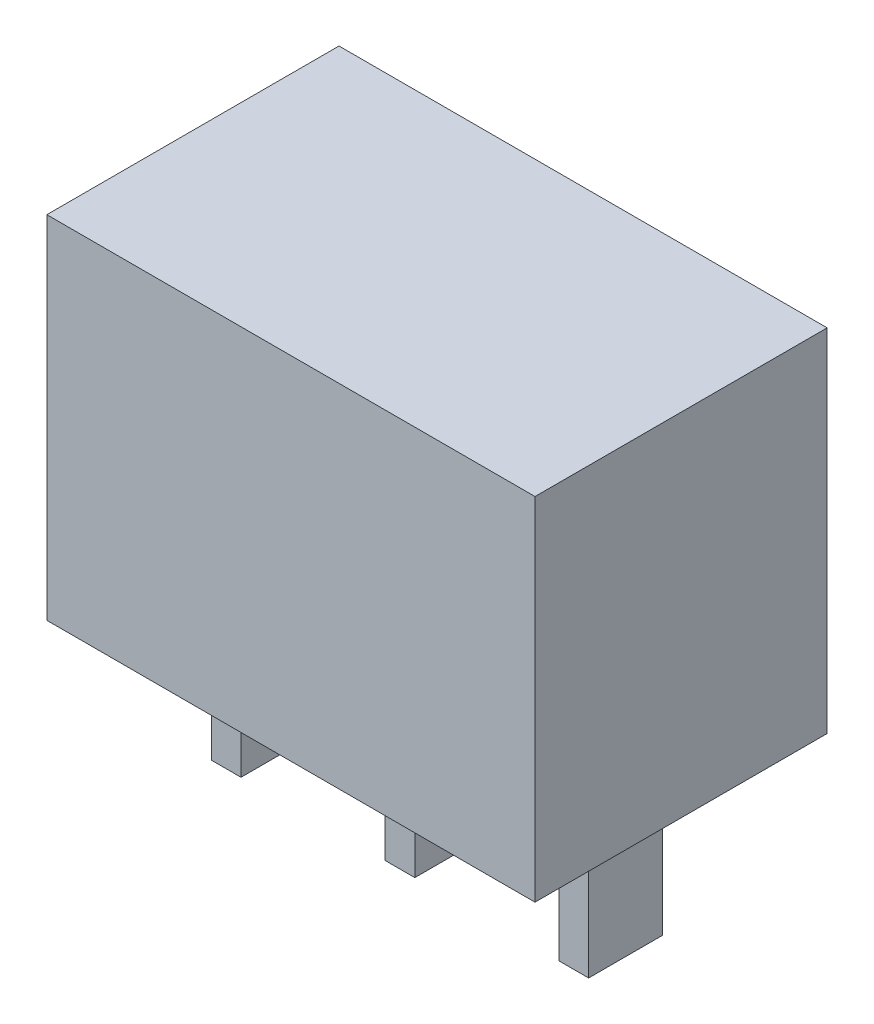
SolidWorks part; units mm, degrees
ref_plane "Front Plane" through (0, 0, 0) normal (0, 0, 1) x (1, 0, 0)
ref_plane "Top Plane" through (0, 0, 0) normal (0, 1, 0) x (1, 0, 0)
ref_plane "Right Plane" through (0, 0, 0) normal (1, 0, 0) x (0, 0, -1)
sketch "Sketch1" plane through (0, 0, 0) normal (0, 1, 0) x (1, 0, 0)
  line L1 (-6.6, 3.95) -> (6.6, 3.95)
  line L2 (-6.6, 3.95) -> (-6.6, -3.95)
  line L3 (-6.6, -3.95) -> (6.6, -3.95)
  line L4 (6.6, 3.95) -> (6.6, -3.95)
  line L5 (-6.6, 3.95) -> (6.6, -3.95) construction
  line L6 (-6.6, -3.95) -> (6.6, 3.95) construction
  point P0 (0, 0)
  dimension "D1" = 13.2
  dimension "D2" = 7.9
extrude "Boss-Extrude1" add sketch "Sketch1" along normal blind 9.5
sketch "Sketch2" plane through (0, 0, 0) normal (0, -1, 0) x (1, 0, 0)
  line L0 (0, 3.95) -> (0, -3.95) construction
  line L1 (-6.6, 3.95) -> (6.6, 3.95) construction
  line L2 (6.6, -3.95) -> (-6.6, -3.95) construction
  line L3 (-6.6, 0) -> (6.6, 0) construction
  line L4 (-6.6, -3.95) -> (-6.6, 3.95) construction
  line L5 (6.6, 3.95) -> (6.6, -3.95) construction
  line L7 (-0.4, 1) -> (0.4, 1)
  line L8 (-0.4, 1) -> (-0.4, -1)
  line L9 (-0.4, -1) -> (0.4, -1)
  line L10 (0.4, 1) -> (0.4, -1)
  line L11 (-0.4, 1) -> (0.4, -1) construction
  line L12 (-0.4, -1) -> (0.4, 1) construction
  line L13 (4.3, 1) -> (5.1, 1)
  line L14 (4.3, 1) -> (4.3, -1)
  line L15 (4.3, -1) -> (5.1, -1)
  line L16 (5.1, 1) -> (5.1, -1)
  line L17 (4.3, 1) -> (5.1, -1) construction
  line L18 (4.3, -1) -> (5.1, 1) construction
  line L19 (-5.1, 1) -> (-4.3, 1)
  line L20 (-5.1, 1) -> (-5.1, -1)
  line L21 (-5.1, -1) -> (-4.3, -1)
  line L22 (-4.3, 1) -> (-4.3, -1)
  line L23 (-5.1, 1) -> (-4.3, -1) construction
  line L24 (-5.1, -1) -> (-4.3, 1) construction
  point P12 (0, 0)
  point P17 (4.7, 0)
  point P23 (-4.7, 0)
  dimension "D1" = 0.8
  dimension "D2" = 0.8
  dimension "D3" = 0.8
  dimension "D4" = 2
  dimension "D5" = 2
  dimension "D6" = 2
  dimension "D7" = 4.7
  dimension "D8" = 4.7
extrude "Boss-Extrude2" add sketch "Sketch2" along normal blind 4
